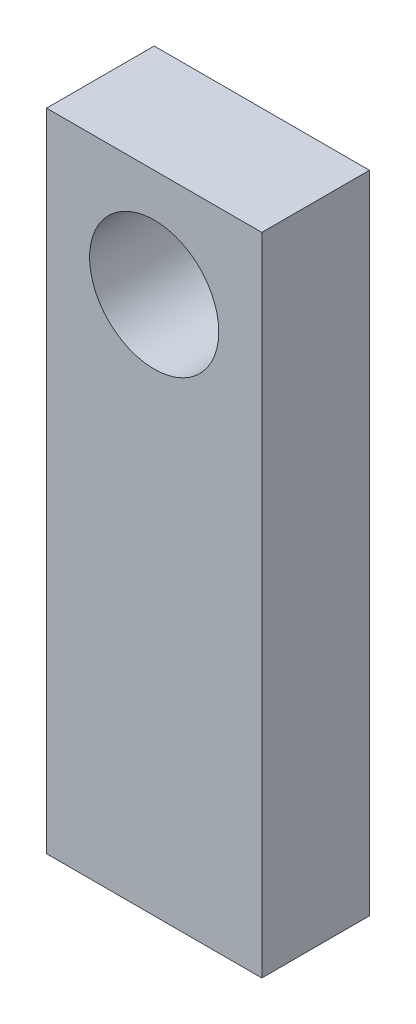
SolidWorks part; units mm, degrees
ref_plane "Front Plane" through (0, 0, 0) normal (0, 0, 1) x (1, 0, 0)
ref_plane "Top Plane" through (0, 0, 0) normal (0, 1, 0) x (1, 0, 0)
ref_plane "Right Plane" through (0, 0, 0) normal (1, 0, 0) x (0, 0, -1)
sketch "Sketch1" plane through (0, 0, 0) normal (0, 0, 1) x (1, 0, 0)
  line L5 (0, 0) -> (12.7, 0)
  line L6 (0, 0) -> (0, -38.1)
  line L7 (0, -38.1) -> (12.7, -38.1)
  line L8 (12.7, 0) -> (12.7, -38.1)
  dimension "D1" = 12.7
  dimension "D2" = 38.1
extrude "Boss-Extrude1" add sketch "Sketch1" along normal blind 6.35
sketch "Sketch2" plane through (0, 0, 6.35) normal (0, 0, 1) x (1, 0, 0)
  line L0 (0, 0) -> (0, -12.7) construction
  line L1 (0, 0) -> (0, -38.1) construction
  line L2 (0, -12.7) -> (12.7, -12.7) construction
  line L3 (12.7, -38.1) -> (12.7, 0) construction
  line L4 (12.7, -12.7) -> (0, 0) construction
  line L5 (0, -12.7) -> (12.7, 0) construction
  circle A0 centre (6.35, -6.35) radius 3.81
  dimension "D1" = 7.62
extrude "Cut-Extrude1" cut sketch "Sketch2" against normal through all both and the other way through all
